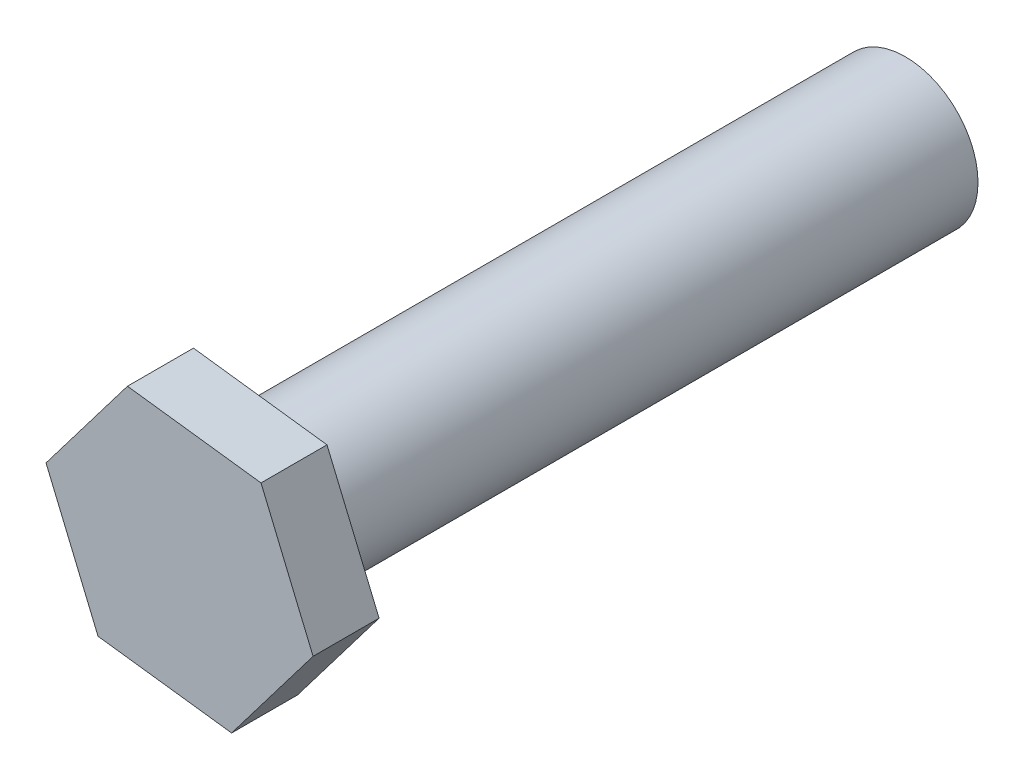
SolidWorks part; units mm, degrees
ref_plane "정면" through (0, 0, 0) normal (0, 0, 1) x (1, 0, 0)
ref_plane "윗면" through (0, 0, 0) normal (0, 1, 0) x (1, 0, 0)
ref_plane "우측면" through (0, 0, 0) normal (1, 0, 0) x (0, 0, -1)
sketch "스케치1" plane through (0, 0, 0) normal (0, 0, 1) x (1, 0, 0)
  circle A0 centre (0, 0) radius 1.65
  dimension "D1" = 3.3
extrude "보스-돌출1" add sketch "스케치1" along normal blind 15
sketch "스케치2" plane through (0, 0, 15) normal (0, 0, -1) x (-1, 0, 0)
  line L1 (1.852, -2.4359) -> (3.0355, 0.386)
  line L2 (3.0355, 0.386) -> (1.1835, 2.8218)
  line L3 (1.1835, 2.8218) -> (-1.852, 2.4359)
  line L4 (-1.852, 2.4359) -> (-3.0355, -0.386)
  line L5 (-3.0355, -0.386) -> (-1.1835, -2.8218)
  line L6 (-1.1835, -2.8218) -> (1.852, -2.4359)
  circle A0 centre (0, 0) radius 2.65 construction
  circle A1 centre (0, 0) radius 1.65 construction
  dimension "D1" = 1
extrude "보스-돌출2" add sketch "스케치2" against normal blind 1.5
